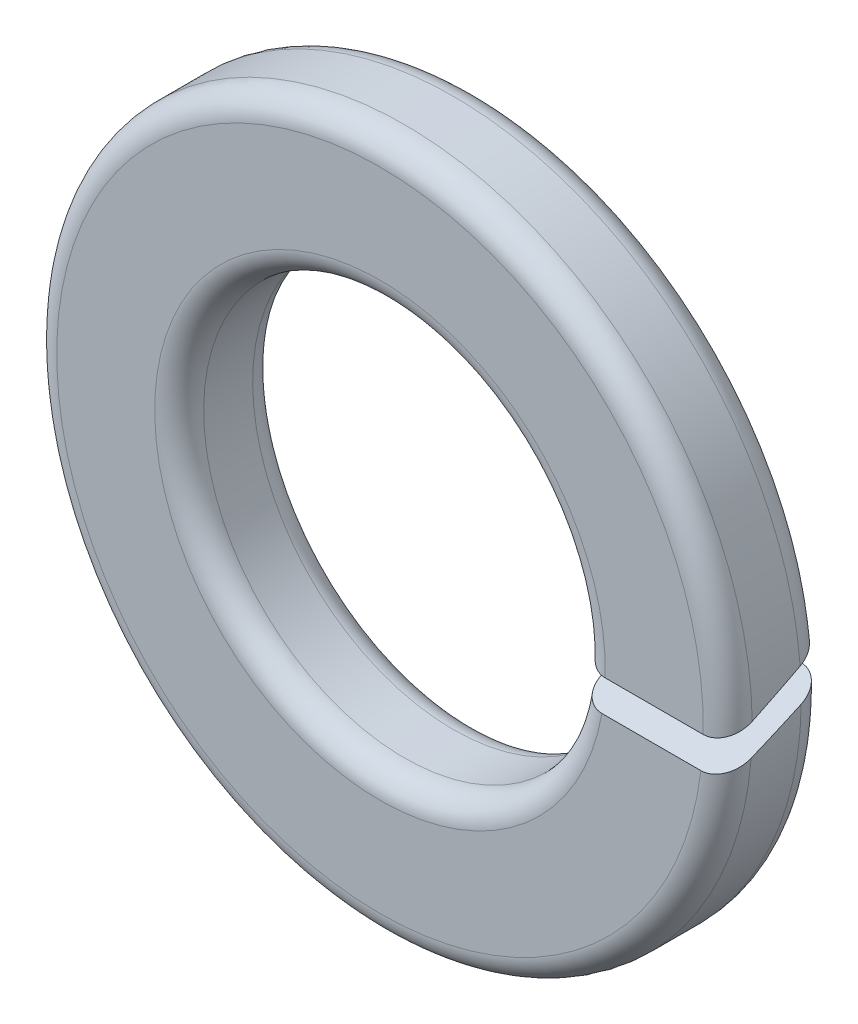
SolidWorks part; units mm, degrees
ref_plane "Přední rovina" through (0, 0, 0) normal (0, 0, 1) x (1, 0, 0)
ref_plane "Vrchní rovina" through (0, 0, 0) normal (0, 1, 0) x (1, 0, 0)
ref_plane "Pravá rovina" through (0, 0, 0) normal (1, 0, 0) x (0, 0, -1)
sketch "Skica1" plane through (0, 0, 0) normal (0, 0, 1) x (1, 0, 0)
  circle A0 centre (0, 0) radius 4.1
  circle A1 centre (0, 0) radius 7.1
  dimension "d1" = 8.2
  dimension "d2" = 14.2
extrude "Vysunout1" add sketch "Skica1" along normal blind 2
fillet "Zaoblit1" radius 0.5 4 edges at (7.1, 0, 0) (7.1, 0, 2) (4.1, 0, 0) (4.1, 0, 2)
sketch "Skica2" plane through (0, 0, 0) normal (1, 0, 0) x (0, 0, -1)
  line L0 (0, 0) -> (-2, 0) construction
  line L1 (-2, 7.1) -> (-2, -7.1) construction
  line L2 (0, 0.1353) -> (-2, -0.7973)
  line L3 (0, -7.1) -> (0, 7.1) construction
  line L4 (0, 0.7973) -> (-2, -0.1353)
  line L5 (0, 0.1353) -> (0, 0.7973)
  line L6 (-2, -0.7973) -> (-2, -0.1353)
  line L7 (0, 0.7973) -> (0, 0) construction
  line L8 (-2, 0) -> (-2, -0.7973) construction
  dimension "D1" = 65
  dimension "D2" = 0.6
extrude "Odebrat vysunutím1" cut sketch "Skica2" along normal through all
equation "\"D2@Skica2\" = \"R@Zaoblit1\" * 1.2"
